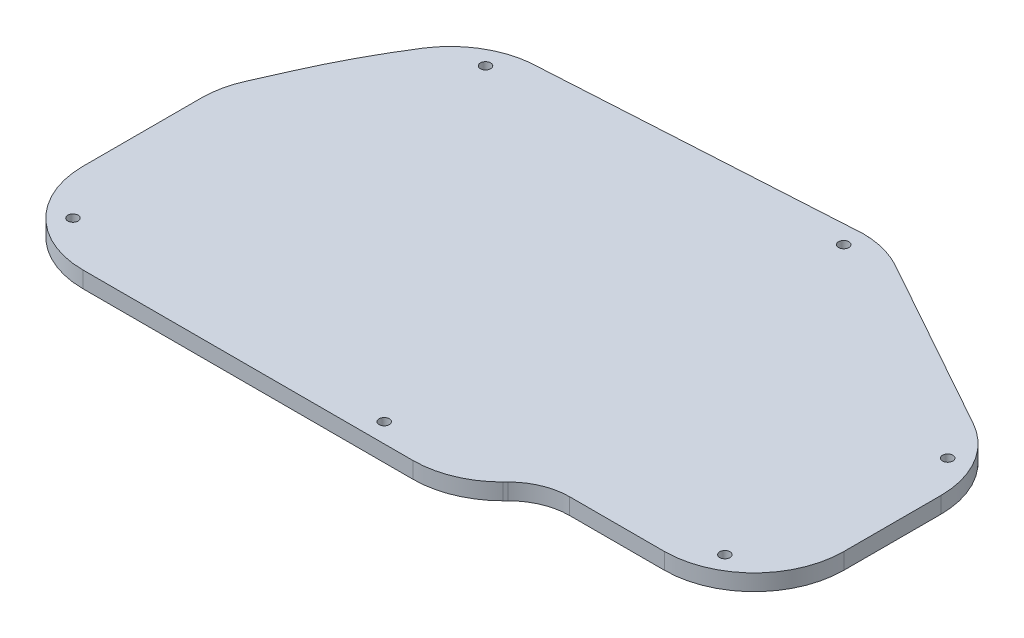
SolidWorks part; units mm, degrees
ref_plane "Front Plane" through (0, 0, 0) normal (0, 0, 1) x (1, 0, 0)
ref_plane "Top Plane" through (0, 0, 0) normal (0, 1, 0) x (1, 0, 0)
ref_plane "Right Plane" through (0, 0, 0) normal (1, 0, 0) x (0, 0, -1)
sketch "Sketch2" plane through (0, 0, 0) normal (0, 1, 0) x (1, 0, 0)
  line L7 (-257.8256, -105.63) -> (-193.4944, -105.63)
  line L8 (-181.1201, -100.5044) -> (-180.6101, -99.9944)
  line L9 (-172.1248, -96.4797) -> (-153.6496, -96.4797)
  line L10 (-136.1496, -78.9797) -> (-136.1496, -60.0821)
  line L11 (-145.1341, -44.7936) -> (-179.4485, -25.681)
  line L12 (-187.9639, -23.4695) -> (-247.3805, -26.968)
  line L13 (-271.0251, -51.648) -> (-273.8196, -57.9411)
  line L14 (-275.3256, -65.0434) -> (-275.3256, -88.13)
  circle A15 centre (-147.2076, -91.1273) radius 1
  circle A16 centre (-141.795, -53.1155) radius 1
  circle A17 centre (-187.9639, -27.2195) radius 1
  arc A18 (-275.3256, -88.13) -> (-257.8256, -105.63) centre (-257.8256, -88.13) ccw
  arc A19 (-193.4944, -105.63) -> (-181.1201, -100.5044) centre (-193.4944, -88.13) ccw
  arc A20 (-172.1248, -96.4797) -> (-180.6101, -99.9944) centre (-172.1248, -108.4797) ccw
  arc A21 (-153.6496, -96.4797) -> (-136.1496, -78.9797) centre (-153.6496, -78.9797) ccw
  arc A22 (-136.1496, -60.0821) -> (-145.1341, -44.7936) centre (-153.6496, -60.0821) ccw
  arc A23 (-179.4485, -25.681) -> (-187.9639, -23.4695) centre (-187.9639, -40.9695) ccw
  arc A24 (-247.3805, -26.968) -> (-262.1548, -35.0887) centre (-247.3805, -44.468) ccw
  arc A25 (-262.1548, -35.0887) -> (-271.0251, -51.648) centre (-154.7153, -103.2964) ccw
  arc A26 (-273.8196, -57.9411) -> (-275.3256, -65.0434) centre (-257.8256, -65.0434) ccw
  circle A27 centre (-253.0515, -31.942) radius 1
  circle A28 centre (-267.5484, -97.8527) radius 1
  circle A29 centre (-202.8547, -101.88) radius 1
extrude "Boss-Extrude1" add sketch "Sketch2" along normal blind 3.175
